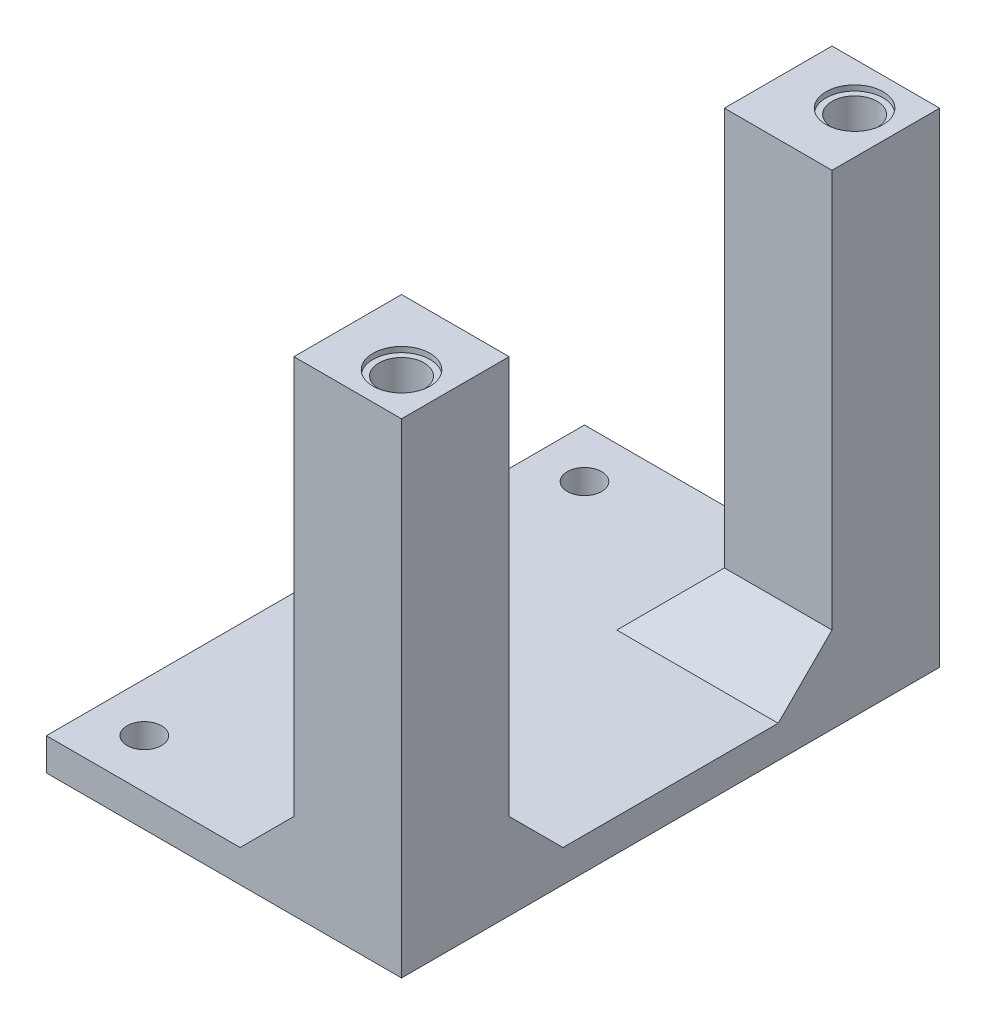
SolidWorks part; units mm, degrees
ref_plane "Front Plane" through (0, 0, 0) normal (0, 0, 1) x (1, 0, 0)
ref_plane "Top Plane" through (0, 0, 0) normal (0, 1, 0) x (1, 0, 0)
ref_plane "Right Plane" through (0, 0, 0) normal (1, 0, 0) x (0, 0, -1)
sketch "Sketch1" plane through (0, 0, 0) normal (0, 1, 0) x (1, 0, 0)
  line L1 (-6.5124, 9.686) -> (1.4876, 9.686)
  line L2 (-6.5124, 9.686) -> (-6.5124, -40.314)
  line L3 (-6.5124, -40.314) -> (1.4876, -40.314)
  line L4 (1.4876, 9.686) -> (1.4876, -40.314)
  line L5 (1.4876, 9.686) -> (26.4876, 9.686)
  line L6 (1.4876, 9.686) -> (1.4876, -40.314)
  line L7 (1.4876, -40.314) -> (26.4876, -40.314)
  line L8 (26.4876, 9.686) -> (26.4876, -40.314)
  circle A0 centre (-1.9624, -35.764) radius 1.6
  circle A1 centre (-1.9624, 5.136) radius 1.6
  dimension "D4" = 3.2
  dimension "D5" = 3.2
  dimension "D6" = 4.55
  dimension "D7" = 4.55
  dimension "D8" = 4.55
  dimension "D9" = 4.55
  dimension "D1" = 8
  dimension "D2" = 50
  dimension "D3" = 25
extrude "Boss-Extrude1" add sketch "Sketch1" along normal blind 3 contours A1 | A0 | L5 L8 L7 L3 L2 L1
sketch "Sketch2" plane through (0, 3, 0) normal (0, 1, 0) x (1, 0, 0)
  line L1 (26.4876, -40.314) -> (16.4876, -40.314)
  line L2 (26.4876, -40.314) -> (26.4876, -30.314)
  line L3 (26.4876, -30.314) -> (16.4876, -30.314)
  line L4 (16.4876, -40.314) -> (16.4876, -30.314)
  line L5 (26.4876, 9.686) -> (16.4876, 9.686)
  line L6 (26.4876, 9.686) -> (26.4876, -0.314)
  line L7 (26.4876, -0.314) -> (16.4876, -0.314)
  line L8 (16.4876, 9.686) -> (16.4876, -0.314)
  dimension "D1" = 10
  dimension "D2" = 10
  dimension "D3" = 10
  dimension "D4" = 10
extrude "Boss-Extrude2" add sketch "Sketch2" along normal blind 42
chamfer "Chamfer1" distance 5 angle 45 4 edges at (16.4876, 3, -4.686) (21.4876, 3, 0.314) (16.4876, 3, 35.314) (21.4876, 3, 30.314)
ref_plane "Plane1" through (0, 45, 0) normal (0, 1, 0) x (1, 0, 0)
sketch "Sketch3" plane through (0, 45, 0) normal (0, 1, 0) x (1, 0, 0)
  line L0 (26.4876, -40.314) -> (26.4876, -30.314) construction
  line L1 (16.4876, -40.314) -> (26.4876, -40.314) construction
  line L2 (26.4876, -0.314) -> (26.4876, 9.686) construction
  line L3 (26.4876, 9.686) -> (16.4876, 9.686) construction
  circle A0 centre (22.5376, -36.364) radius 2.1
  circle A1 centre (22.5376, 5.736) radius 2.1
  dimension "D1" = 4.2
  dimension "D3" = 3.95
  dimension "D4" = 4.2
  dimension "D6" = 3.95
  dimension "D2" = 3.95
  dimension "D5" = 3.95
extrude "Cut-Extrude1" cut sketch "Sketch3" against normal blind 52
sketch "Sketch4" plane through (0, 45, 0) normal (0, 1, 0) x (1, 0, 0)
  circle A0 centre (22.5376, -36.364) radius 2.65
  circle A1 centre (22.5376, 5.736) radius 2.65
  dimension "D1" = 5.3
  dimension "D2" = 5.3
extrude "Cut-Extrude2" cut sketch "Sketch4" against normal blind 0.5
ref_plane "Plane2" through (0, 22.5, 0) normal (0, -1, 0) x (-1, 0, 0)
mirror "Mirror1" about plane through (0, 22.5, 0) normal (0, -1, 0) of "Cut-Extrude2"
